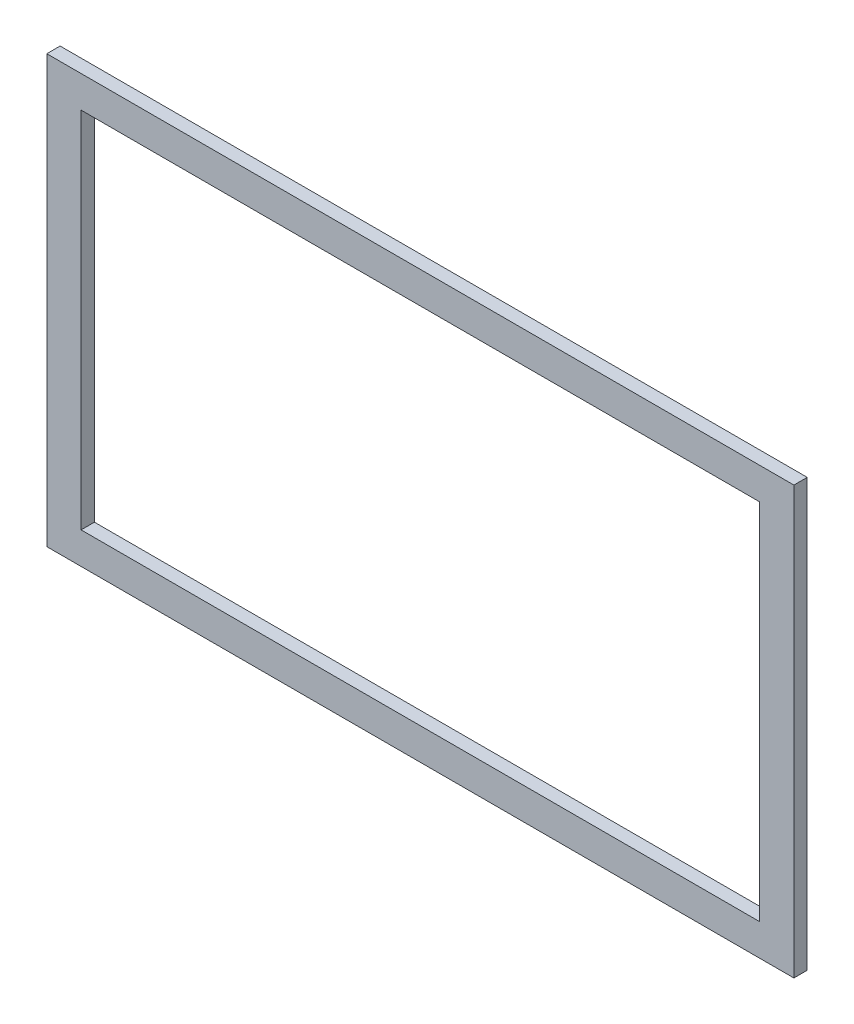
SolidWorks part; units mm, degrees
ref_plane "Alzado" through (0, 0, 0) normal (0, 0, 1) x (1, 0, 0)
ref_plane "Planta" through (0, 0, 0) normal (0, 1, 0) x (1, 0, 0)
ref_plane "Vista lateral" through (0, 0, 0) normal (1, 0, 0) x (0, 0, -1)
sketch "Croquis1" plane through (0, 0, 0) normal (0, 0, 1) x (1, 0, 0)
  line L1 (-14, -8) -> (14, -8)
  line L2 (-14, -8) -> (-14, 8)
  line L3 (-14, 8) -> (14, 8)
  line L4 (14, -8) -> (14, 8)
  line L5 (-14, -8) -> (14, 8) construction
  line L6 (-14, 8) -> (14, -8) construction
  point P0 (0, 0)
  dimension "D1" = 28
  dimension "D2" = 16
extrude "Saliente-Extruir2" add sketch "Croquis1" along normal blind 0.5 contours L3 L4 L1 L2
sketch "Croquis3" plane through (0, 0, 0.5) normal (0, 0, 1) x (1, 0, 0)
  line L1 (-12.7133, -6.8123) -> (12.7133, -6.8123)
  line L2 (-12.7133, -6.8123) -> (-12.7133, 6.8123)
  line L3 (-12.7133, 6.8123) -> (12.7133, 6.8123)
  line L4 (12.7133, -6.8123) -> (12.7133, 6.8123)
  line L5 (-12.7133, -6.8123) -> (12.7133, 6.8123) construction
  line L6 (-12.7133, 6.8123) -> (12.7133, -6.8123) construction
  point P0 (0, 0)
extrude "Cortar-Extruir2" cut sketch "Croquis3" against normal through all
